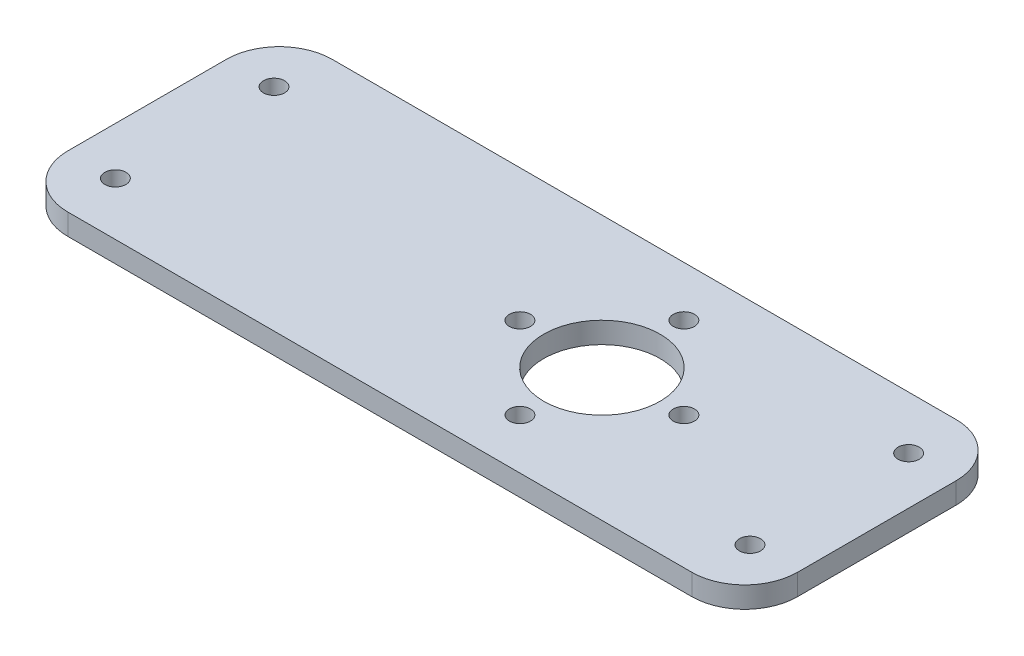
SolidWorks part; units mm, degrees
ref_plane "Front" through (0, 0, 0) normal (0, 0, 1) x (1, 0, 0)
ref_plane "Top" through (0, 0, 0) normal (0, 1, 0) x (1, 0, 0)
ref_plane "Right" through (0, 0, 0) normal (1, 0, 0) x (0, 0, -1)
sketch "草图1" plane through (0, 0, 0) normal (0, 1, 0) x (1, 0, 0)
  line L1 (52, -25) -> (-91, -25)
  line L2 (52, -25) -> (52, 25)
  line L3 (52, 25) -> (-91, 25)
  line L4 (-91, -25) -> (-91, 25)
  circle A0 centre (15.5, 0) radius 2
  circle A1 centre (0, 0) radius 11
  circle A2 centre (43, 15) radius 2
  circle A3 centre (43, -15) radius 2
  circle A4 centre (0, -15.5) radius 2
  circle A5 centre (0, 15.5) radius 2
  circle A6 centre (0, 0) radius 11
  circle A7 centre (-15.5, 0) radius 2
  circle A8 centre (0, 0) radius 11
  circle A9 centre (0, 0) radius 11
  point P0 (0, 0)
  point P5 (0, 0)
  point P12 (52, 0)
  point P28 (0, 0)
  point P30 (0, 0)
  dimension "D5" = 52
  dimension "D6" = 4
  dimension "D7" = 4
  dimension "D8" = 4
  dimension "D9" = 9
  dimension "D10" = 4
  dimension "D12" = 22
  dimension "D4" = 9
  dimension "D11" = 10
  dimension "D1" = 50
  dimension "D2" = 143
  dimension "D3" = 30
extrude "凸台-拉伸1" add sketch "草图1" along normal blind 4 contours L4 L1 L2 L3 A7 A5 A4 A3 A2 A1 A0
sketch "草图4" plane through (0, 4, 0) normal (0, 1, 0) x (1, 0, 0)
  line L0 (-91, 25) -> (-86, 25)
  line L1 (52, 25) -> (-91, 25) construction
  line L2 (-86, 25) -> (-86, -25)
  line L3 (52, -25) -> (-91, -25) construction
  line L4 (-86, -25) -> (-91, -25)
  line L5 (-91, -25) -> (-91, 25)
  dimension "D1" = 5
extrude "切除-拉伸3" cut sketch "草图4" against normal through all
sketch "草图5" plane through (0, 4, 0) normal (0, 1, 0) x (1, 0, 0)
  line L0 (-86, -25) -> (-86, 25) construction
  line L1 (52, -25) -> (-86, -25) construction
  circle A0 centre (-77, 15) radius 2
  circle A1 centre (-77, -15) radius 2
  dimension "D1" = 30
  dimension "D2" = 9
  dimension "D3" = 10
  dimension "D4" = 4
  dimension "D5" = 4
  dimension "D6" = 9
extrude "切除-拉伸4" cut sketch "草图5" against normal through all
fillet "圆角1" radius 10 4 edges at (-86, 2, -25) (-86, 2, 25) (52, 2, 25) (52, 2, -25)
